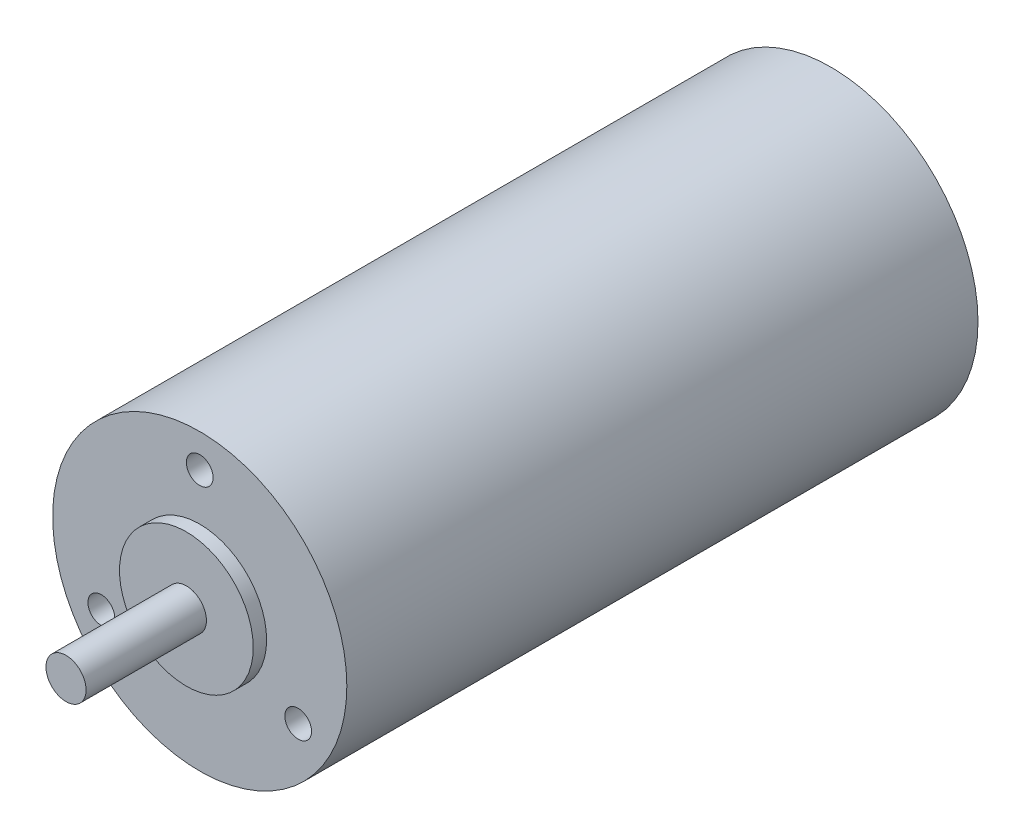
SolidWorks part; units mm, degrees
ref_plane "Front Plane" through (0, 0, 0) normal (0, 0, 1) x (1, 0, 0)
ref_plane "Top Plane" through (0, 0, 0) normal (0, 1, 0) x (1, 0, 0)
ref_plane "Right Plane" through (0, 0, 0) normal (1, 0, 0) x (0, 0, -1)
sketch "Sketch1" plane through (0, 0, 0) normal (0, 0, 1) x (1, 0, 0)
  circle A0 centre (0, 0) radius 11
  dimension "D1" = 22
extrude "Boss-Extrude1" add sketch "Sketch1" against normal blind 47.2
sketch "Sketch2" plane through (0, 0, 0) normal (0, 0, 1) x (1, 0, 0)
  circle A0 centre (0, 0) radius 5
  dimension "D1" = 10
extrude "Boss-Extrude2" add sketch "Sketch2" along normal blind 1 from surface at 0 starting at face at (11, 0, 0)
sketch "Sketch3" plane through (0, 0, 0) normal (0, 0, 1) x (1, 0, 0)
  circle A0 centre (0, 0) radius 1.5
  dimension "D1" = 3
extrude "Boss-Extrude3" add sketch "Sketch3" along normal blind 10 from surface at 0 starting at face at (5, 0, 0)
sketch "Sketch4" plane through (0, 0, 0) normal (0, 0, 1) x (1, 0, 0)
  line L0 (0, 0) -> (0, 8.3448) construction
  circle A0 centre (0, 0) radius 8.5 construction
  circle A1 centre (0, 8.5) radius 1
  circle A2 centre (7.3612, -4.25) radius 1
  circle A3 centre (-7.3612, -4.25) radius 1
  point P12 (0, 0)
  dimension "D1" = 17
  dimension "D2" = 2
  dimension "D3" = 3
extrude "Cut-Extrude1" cut sketch "Sketch4" against normal blind 2.5
